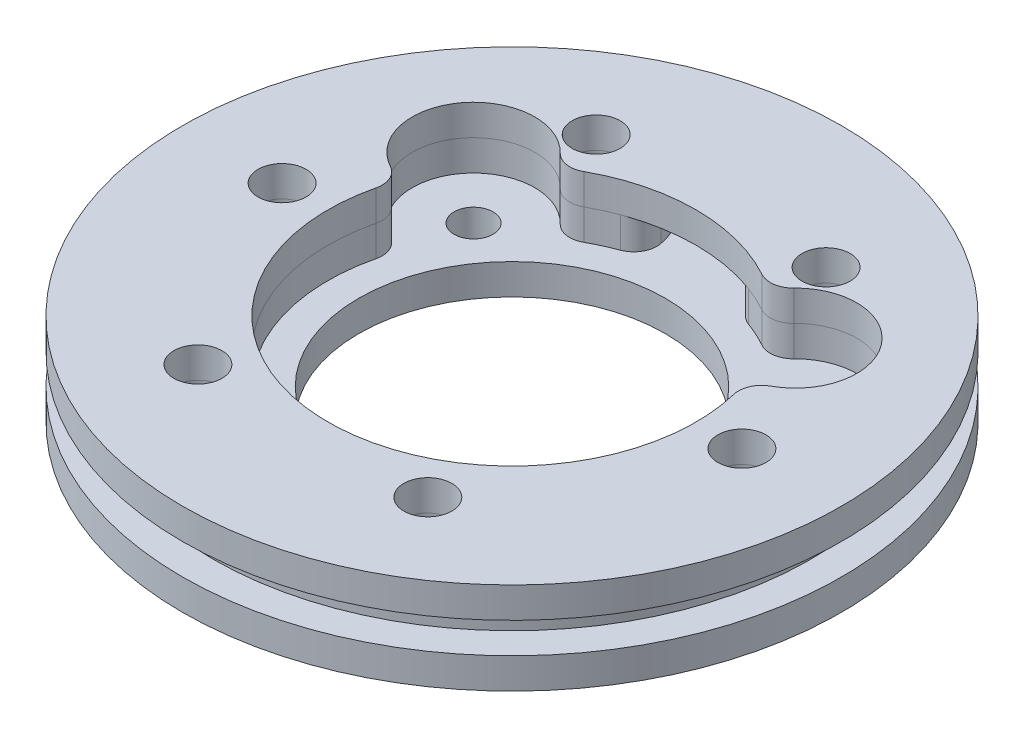
SolidWorks part; units mm, degrees
material "6061-T6 (SS)"
ref_plane "Front Plane" through (0, 0, 0) normal (0, 0, 1) x (1, 0, 0)
ref_plane "Top Plane" through (0, 0, 0) normal (0, 1, 0) x (1, 0, 0)
ref_plane "Right Plane" through (0, 0, 0) normal (1, 0, 0) x (0, 0, -1)
sketch "Sketch1" plane through (0, 0, 0) normal (0, 1, 0) x (1, 0, 0)
  line L0 (0, 0) -> (0, 30.9562) construction
  line L1 (23.8125, 0) -> (11.9062, 20.6222) construction
  line L2 (11.9062, 20.6222) -> (-11.9063, 20.6222) construction
  line L3 (-11.9063, 20.6222) -> (-23.8125, 0) construction
  line L4 (-23.8125, 0) -> (-11.9062, -20.6222) construction
  line L5 (-11.9062, -20.6222) -> (11.9063, -20.6222) construction
  line L6 (11.9063, -20.6222) -> (23.8125, 0) construction
  line L7 (-12.9213, 19.05) -> (12.9213, 19.05) construction
  circle A0 centre (0, 0) radius 30.9562
  circle A1 centre (0, 0) radius 19.05
  circle A2 centre (0, 0) radius 23.8125 construction
  circle A3 centre (0, 0) radius 20.6222 construction
  circle A4 centre (23.8125, 0) radius 2.4892
  circle A5 centre (11.9062, 20.6222) radius 2.4892
  circle A6 centre (-11.9063, 20.6222) radius 2.4892
  circle A7 centre (-23.8125, 0) radius 2.4892
  circle A8 centre (-11.9062, -20.6222) radius 2.4892
  circle A9 centre (11.9063, -20.6222) radius 2.4892
  arc A10 (-17.3769, 25.619) -> (-5.0122, 18.3788) centre (-12.9213, 19.05) cw
  arc A11 (17.3769, 25.619) -> (5.0122, 18.3788) centre (12.9213, 19.05) ccw
  dimension "D1" = 38.1
  dimension "D2" = 61.9125
  dimension "D3" = 47.625
  dimension "D4" = 4.9784
  dimension "D5" = 7.9375
extrude "Boss-Extrude1" add sketch "Sketch1" against normal blind 3.175 contours A0 A11 A1 A10 A9 A8 A7 A6 A5 A4
sketch "Sketch2" plane through (0, -3.175, 0) normal (0, -1, 0) x (-1, 0, 0)
  circle A0 centre (23.8125, 0) radius 2.4892 construction
  circle A1 centre (11.9063, 20.6222) radius 2.4892 construction
  circle A2 centre (11.9062, -20.6222) radius 2.4892 construction
  circle A3 centre (-11.9063, -20.6222) radius 2.4892 construction
  circle A4 centre (-23.8125, 0) radius 2.4892 construction
  circle A5 centre (-11.9062, 20.6222) radius 2.4892 construction
  circle A6 centre (0, 0) radius 34.1313
  circle A18 centre (-11.9062, 20.6222) radius 2.4892
  circle A19 centre (-23.8125, 0) radius 2.4892
  circle A20 centre (-11.9063, -20.6222) radius 2.4892
  circle A21 centre (11.9062, -20.6222) radius 2.4892
  circle A22 centre (11.9063, 20.6222) radius 2.4892
  circle A23 centre (23.8125, 0) radius 2.4892
  circle A24 centre (0, 0) radius 15.875
  circle A25 centre (16.6688, 12.6847) radius 2.0193
  circle A26 centre (-16.6687, 12.6847) radius 2.0193
  dimension "D1" = 31.75
  dimension "D3" = 68.2625
  dimension "D4" = 4.0386
  dimension "D2" = 7.9375
  dimension "D5" = 4.7625
  dimension "D6" = 4.7625
extrude "Boss-Extrude2" add sketch "Sketch2" along normal blind 3.175 separate body contours A6
sketch "Sketch3" plane through (0, 0, 0) normal (0, 1, 0) x (1, 0, 0)
  circle A0 centre (-16.6688, 12.6847) radius 6.35
  circle A1 centre (16.6687, 12.6847) radius 6.35
  dimension "D1" = 12.7
extrude "Cut-Extrude1" cut sketch "Sketch3" against normal up to surface (3.175 mm away) up to face at (0, -3.175, -34.1313)
sketch "Sketch4" plane through (0, 0, 0) normal (0, 1, 0) x (1, 0, 0)
  circle A0 centre (0, 0) radius 34.1313 construction
  circle A1 centre (0, 0) radius 34.1313
  arc A3 (-17.9214, 6.4595) -> (17.9214, 6.4595) centre (0, 0) ccw construction
  circle A4 centre (11.9062, 20.6222) radius 2.4892 construction
  circle A5 centre (23.8125, 0) radius 2.4892 construction
  circle A6 centre (11.9063, -20.6222) radius 2.4892 construction
  circle A7 centre (-11.9062, -20.6222) radius 2.4892 construction
  circle A8 centre (-23.8125, 0) radius 2.4892 construction
  circle A9 centre (-11.9063, 20.6222) radius 2.4892 construction
  circle A10 centre (11.9062, 20.6222) radius 2.4892
  circle A11 centre (23.8125, 0) radius 2.4892
  circle A12 centre (11.9063, -20.6222) radius 2.4892
  circle A13 centre (-11.9062, -20.6222) radius 2.4892
  circle A14 centre (-23.8125, 0) radius 2.4892
  circle A15 centre (-11.9063, 20.6222) radius 2.4892
  arc A17 (-17.9214, 6.4595) -> (17.9214, 6.4595) centre (0, 0) ccw
  arc A19 (17.9214, 6.4595) -> (11.0026, 15.5514) centre (16.6687, 12.6847) ccw construction
  arc A20 (11.0026, 15.5514) -> (5.0122, 18.3788) centre (0, 0) ccw construction
  arc A21 (-5.0122, 18.3788) -> (-11.0026, 15.5514) centre (0, 0) ccw construction
  arc A22 (17.9214, 6.4595) -> (11.0026, 15.5514) centre (16.6687, 12.6847) ccw
  arc A23 (11.0026, 15.5514) -> (5.0122, 18.3788) centre (0, 0) ccw
  arc A24 (-5.0122, 18.3788) -> (-11.0026, 15.5514) centre (0, 0) ccw
  arc A25 (-11.0026, 15.5514) -> (-17.9214, 6.4595) centre (-16.6688, 12.6847) ccw construction
  arc A26 (-11.0026, 15.5514) -> (-17.9214, 6.4595) centre (-16.6688, 12.6847) ccw
  arc A27 (5.0122, 18.3788) -> (-5.0122, 18.3788) centre (0, 0) ccw
  arc A28 (-5.0122, 18.3788) -> (-17.3769, 25.619) centre (-12.9213, 19.05) ccw construction
  arc M2 (-17.9214, 6.4595) -> (-11.0026, 15.5514) centre (-16.6688, 12.6847) cw
  arc M3 (-11.0026, 15.5514) -> (-5.0122, 18.3788) centre (0, 0) cw
  arc M4 (-5.0122, 18.3788) -> (-17.3769, 25.619) centre (-12.9213, 19.05) ccw
  arc M5 (-17.3769, 25.619) -> (17.3769, 25.619) centre (0, 0) ccw
  arc M6 (17.3769, 25.619) -> (5.0122, 18.3788) centre (12.9213, 19.05) ccw
  arc M7 (5.0122, 18.3788) -> (11.0026, 15.5514) centre (0, 0) cw
  arc M8 (11.0026, 15.5514) -> (17.9214, 6.4595) centre (16.6687, 12.6847) cw
  arc M9 (17.9214, 6.4595) -> (-17.9214, 6.4595) centre (0, 0) cw
  circle M10 centre (11.9063, -20.6222) radius 2.4892
  circle M11 centre (-11.9062, -20.6222) radius 2.4892
  circle M12 centre (-23.8125, 0) radius 2.4892
  circle M13 centre (-11.9063, 20.6222) radius 2.4892
  circle M14 centre (11.9062, 20.6222) radius 2.4892
  circle M15 centre (23.8125, 0) radius 2.4892
extrude "Boss-Extrude3" add sketch "Sketch4" along normal blind 3.175 separate body contours M9 M2 M3 M4 M5 M6 M7 M8 M10 M12 M14 M15 M13 M11 | A1 A27 M6 M5 M4
fillet "Fillet2" radius 2.3813 6 edges at (-5.0122, -1.5875, -18.3788) (5.0122, -1.5875, -18.3788) (17.9214, -1.5875, -6.4595) (11.0026, -1.5875, -15.5514) (-11.0026, -1.5875, -15.5514) (-17.9214, -1.5875, -6.4595)
ref_plane "Plane1" through (0, -1.5875, 0) normal (0, 1, 0) x (1, 0, 0)
fillet "Fillet3" radius 2.3813 4 edges at (17.9214, 1.5875, -6.4595) (11.0026, 1.5875, -15.5514) (-11.0026, 1.5875, -15.5514) (-17.9214, 1.5875, -6.4595)
